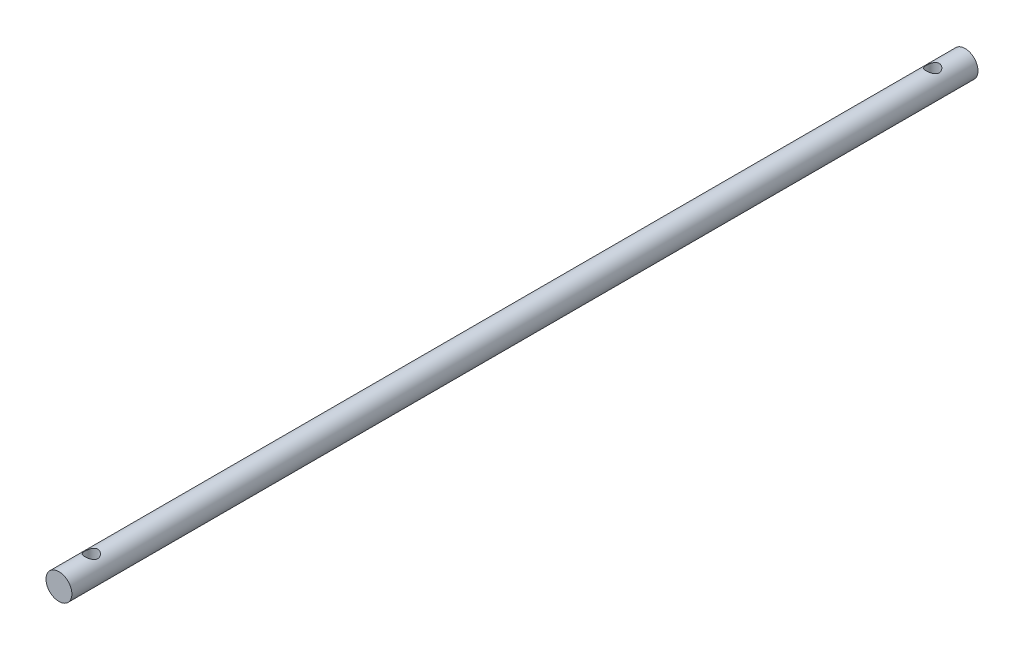
SolidWorks part; units mm, degrees
material "Plain Carbon Steel"
ref_plane "Front Plane" through (0, 0, 0) normal (0, 0, 1) x (1, 0, 0)
ref_plane "Top Plane" through (0, 0, 0) normal (0, 1, 0) x (1, 0, 0)
ref_plane "Right Plane" through (0, 0, 0) normal (1, 0, 0) x (0, 0, -1)
sketch "Sketch1" plane through (0, 0, 0) normal (0, 0, 1) x (1, 0, 0)
  circle A0 centre (0, 0) radius 4
extrude "Extrude1" add sketch "Sketch1" along normal blind 280
hole_wizard "Ø4.0 (4) Diameter Hole1" positions "Sketch4" profile "Sketch3" hole size "Ø4.0" standard "Ansi Metric"
sketch "Sketch4" plane through (0, 0, 0) normal (0, 1, 0) x (1, 0, 0)
  line L0 (4, 0) -> (-4, 0) construction
  line L1 (-4, -280) -> (4, -280) construction
  point P1 (0, -10)
  point P3 (0, -270)
  dimension "D1" = 10
  dimension "D2" = 10
sketch "Sketch3" plane through (0, 0, 10) normal (1, 0, 0) x (0, 0, -1)
  line L0 (0, 0) -> (0, 4)
  line L1 (0, 4) -> (2, 4)
  line L2 (2, 4) -> (2, 0)
  line L5 (2, 0) -> (0, 0)
  line L11 (0, -6.35) -> (0, 107.95) construction
  dimension "Thru Hole Dia." = 4
  dimension "Thru Hole Depth" = 4
